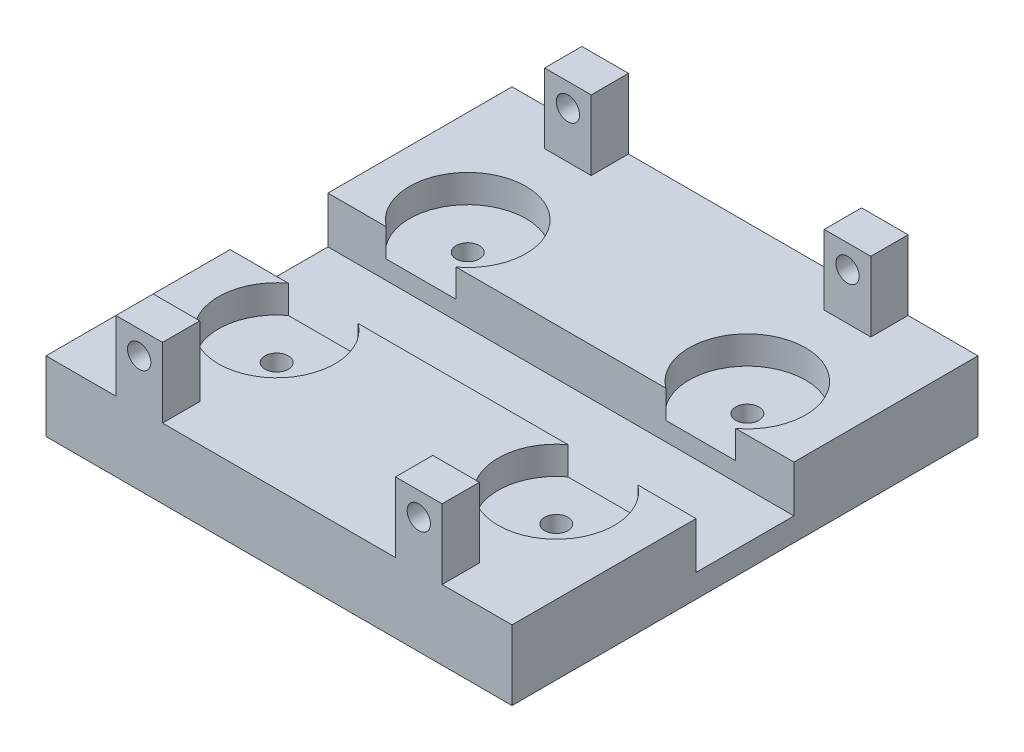
SolidWorks part; units mm, degrees
ref_plane "Front Plane" through (0, 0, 0) normal (0, 0, 1) x (1, 0, 0)
ref_plane "Top Plane" through (0, 0, 0) normal (0, 1, 0) x (1, 0, 0)
ref_plane "Right Plane" through (0, 0, 0) normal (1, 0, 0) x (0, 0, -1)
sketch "Sketch1" plane through (0, 0, 0) normal (0, 1, 0) x (1, 0, 0)
  line L1 (-907.2662, 39.6204) -> (92.7338, 39.6204)
  line L2 (-907.2662, 39.6204) -> (-907.2662, -960.3796)
  line L3 (-907.2662, -960.3796) -> (92.7338, -960.3796)
  line L4 (92.7338, 39.6204) -> (92.7338, -960.3796)
  dimension "D1" = 1000
  dimension "D2" = 1000
extrude "Boss-Extrude1" add sketch "Sketch1" along normal blind 300
sketch "Sketch2" plane through (0, 300, 0) normal (0, 1, 0) x (1, 0, 0)
  line L0 (-907.2662, 39.6204) -> (-907.2662, -960.3796) construction
  line L1 (-907.2662, -560.3796) -> (92.7338, -560.3796)
  line L2 (-907.2662, -560.3796) -> (-907.2662, -360.3796)
  line L3 (-907.2662, -360.3796) -> (92.7338, -360.3796)
  line L4 (92.7338, -560.3796) -> (92.7338, -360.3796)
  line L5 (92.7338, -960.3796) -> (92.7338, 39.6204) construction
  line L6 (92.7338, 39.6204) -> (-907.2662, 39.6204) construction
  line L7 (-907.2662, -960.3796) -> (92.7338, -960.3796) construction
  dimension "D1" = 400
  dimension "D2" = 400
extrude "Cut-Extrude1" cut sketch "Sketch2" against normal blind 100
other "Move Face1" face at (-407.2662, 0, 460.3796) parameters "D1"=150
scale "Scale1" bodies to scale 104 scale about centroid uniform scaling yes scale factor 0.1
sketch "Sketch5" plane through (0, 229.0385, 0) normal (0, 1, 0) x (1, 0, 0)
  line L0 (-457.2662, -410.3796) -> (-457.2662, -450.3796) construction
  line L1 (-357.2662, -410.3796) -> (-457.2662, -410.3796) construction
  circle A0 centre (-437.2662, -439.8796) radius 12.5
  dimension "D1" = 20
  dimension "D2" = 29.5
  dimension "D3" = 25
extrude "Cut-Extrude4" cut sketch "Sketch5" against normal blind 6 contours A0
sketch "Sketch11" plane through (0, 229.0385, 0) normal (0, 1, 0) x (1, 0, 0)
  line L0 (-357.2662, -450.3796) -> (-357.2662, -410.3796) construction
  line L1 (-357.2662, -410.3796) -> (-457.2662, -410.3796) construction
  circle A0 centre (-377.2662, -439.8796) radius 12.5
  dimension "D1" = 20
  dimension "D2" = 29.5
  dimension "D3" = 25
extrude "Cut-Extrude5" cut sketch "Sketch11" against normal blind 6 contours A0
sketch "Sketch12" plane through (0, 229.0385, 0) normal (0, 1, 0) x (1, 0, 0)
  line L0 (-357.2662, -510.3796) -> (-357.2662, -470.3796) construction
  line L1 (-457.2662, -510.3796) -> (-357.2662, -510.3796) construction
  circle A0 centre (-377.2662, -480.8796) radius 12.5
  dimension "D1" = 20
  dimension "D2" = 29.5
  dimension "D3" = 25
extrude "Cut-Extrude6" cut sketch "Sketch12" against normal blind 6 contours A0
sketch "Sketch13" plane through (0, 229.0385, 0) normal (0, 1, 0) x (1, 0, 0)
  line L0 (-457.2662, -470.3796) -> (-457.2662, -510.3796) construction
  line L1 (-457.2662, -510.3796) -> (-357.2662, -510.3796) construction
  circle A0 centre (-437.2662, -480.8796) radius 12.5
  dimension "D1" = 20
  dimension "D2" = 29.5
  dimension "D3" = 25
extrude "Cut-Extrude7" cut sketch "Sketch13" against normal blind 6 contours A0
sketch "Sketch14" plane through (0, 214.0385, 0) normal (0, -1, 0) x (-1, 0, 0)
  line L0 (357.2662, -510.3796) -> (357.2662, -410.3796) construction
  line L1 (377.2662, -444.5273) -> (381.2912, -442.2034)
  line L2 (381.2912, -442.2034) -> (381.2912, -437.5558)
  line L3 (381.2912, -437.5558) -> (377.2662, -435.2319)
  line L4 (377.2662, -435.2319) -> (373.2412, -437.5558)
  line L5 (373.2412, -437.5558) -> (373.2412, -442.2034)
  line L6 (373.2412, -442.2034) -> (377.2662, -444.5273)
  line L7 (357.2662, -410.3796) -> (457.2662, -410.3796) construction
  circle A0 centre (377.2662, -439.8796) radius 4.025 construction
  dimension "D3" = 8.05
  dimension "D1" = 20
  dimension "D2" = 29.5
extrude "Cut-Extrude8" cut sketch "Sketch14" against normal blind 3
sketch "Sketch15" plane through (0, 217.0385, 0) normal (0, -1, 0) x (-1, 0, 0)
  line L0 (357.2662, -510.3796) -> (357.2662, -410.3796) construction
  line L1 (357.2662, -410.3796) -> (457.2662, -410.3796) construction
  circle A0 centre (377.2662, -439.8796) radius 2.5
  dimension "D3" = 5
  dimension "D1" = 20
  dimension "D2" = 29.5
extrude "Cut-Extrude9" cut sketch "Sketch15" against normal blind 16
sketch "Sketch16" plane through (0, 214.0385, 0) normal (0, -1, 0) x (-1, 0, 0)
  line L0 (457.2662, -410.3796) -> (457.2662, -510.3796) construction
  line L1 (437.2662, -444.5273) -> (441.2912, -442.2034)
  line L2 (441.2912, -442.2034) -> (441.2912, -437.5558)
  line L3 (441.2912, -437.5558) -> (437.2662, -435.2319)
  line L4 (437.2662, -435.2319) -> (433.2412, -437.5558)
  line L5 (433.2412, -437.5558) -> (433.2412, -442.2034)
  line L6 (433.2412, -442.2034) -> (437.2662, -444.5273)
  line L7 (357.2662, -410.3796) -> (457.2662, -410.3796) construction
  circle A0 centre (437.2662, -439.8796) radius 4.025 construction
  dimension "D3" = 8.05
  dimension "D1" = 20
  dimension "D2" = 29.5
extrude "Cut-Extrude10" cut sketch "Sketch16" against normal blind 3
sketch "Sketch17" plane through (0, 217.0385, 0) normal (0, -1, 0) x (-1, 0, 0)
  line L0 (457.2662, -410.3796) -> (457.2662, -510.3796) construction
  line L1 (357.2662, -410.3796) -> (457.2662, -410.3796) construction
  circle A0 centre (437.2662, -439.8796) radius 2.5
  dimension "D1" = 20
  dimension "D3" = 5
  dimension "D2" = 29.5
extrude "Cut-Extrude11" cut sketch "Sketch17" against normal blind 10
sketch "Sketch18" plane through (0, 214.0385, 0) normal (0, -1, 0) x (-1, 0, 0)
  line L0 (357.2662, -510.3796) -> (357.2662, -410.3796) construction
  line L1 (377.2662, -485.5273) -> (381.2912, -483.2034)
  line L2 (381.2912, -483.2034) -> (381.2912, -478.5558)
  line L3 (381.2912, -478.5558) -> (377.2662, -476.2319)
  line L4 (377.2662, -476.2319) -> (373.2412, -478.5558)
  line L5 (373.2412, -478.5558) -> (373.2412, -483.2034)
  line L6 (373.2412, -483.2034) -> (377.2662, -485.5273)
  line L7 (457.2662, -510.3796) -> (357.2662, -510.3796) construction
  circle A0 centre (377.2662, -480.8796) radius 4.025 construction
  dimension "D3" = 8.05
  dimension "D1" = 20
  dimension "D2" = 29.5
extrude "Cut-Extrude12" cut sketch "Sketch18" against normal blind 3
sketch "Sketch19" plane through (0, 217.0385, 0) normal (0, -1, 0) x (-1, 0, 0)
  line L0 (357.2662, -510.3796) -> (357.2662, -410.3796) construction
  line L1 (457.2662, -510.3796) -> (357.2662, -510.3796) construction
  circle A0 centre (377.2662, -480.8796) radius 2.5
  dimension "D3" = 5
  dimension "D1" = 20
  dimension "D2" = 29.5
extrude "Cut-Extrude13" cut sketch "Sketch19" against normal blind 10
sketch "Sketch20" plane through (0, 214.0385, 0) normal (0, -1, 0) x (-1, 0, 0)
  line L0 (457.2662, -410.3796) -> (457.2662, -510.3796) construction
  line L1 (437.2662, -485.5273) -> (441.2912, -483.2034)
  line L2 (441.2912, -483.2034) -> (441.2912, -478.5558)
  line L3 (441.2912, -478.5558) -> (437.2662, -476.2319)
  line L4 (437.2662, -476.2319) -> (433.2412, -478.5558)
  line L5 (433.2412, -478.5558) -> (433.2412, -483.2034)
  line L6 (433.2412, -483.2034) -> (437.2662, -485.5273)
  line L7 (457.2662, -510.3796) -> (357.2662, -510.3796) construction
  circle A0 centre (437.2662, -480.8796) radius 4.025 construction
  dimension "D3" = 8.05
  dimension "D1" = 20
  dimension "D2" = 29.5
extrude "Cut-Extrude14" cut sketch "Sketch20" against normal blind 3
sketch "Sketch21" plane through (0, 217.0385, 0) normal (0, -1, 0) x (-1, 0, 0)
  line L0 (457.2662, -410.3796) -> (457.2662, -510.3796) construction
  line L1 (457.2662, -510.3796) -> (357.2662, -510.3796) construction
  circle A0 centre (437.2662, -480.8796) radius 2.5
  dimension "D3" = 5
  dimension "D1" = 20
  dimension "D2" = 29.5
extrude "Cut-Extrude15" cut sketch "Sketch21" against normal blind 10
sketch "Sketch27" plane through (0, 229.0385, 0) normal (0, 1, 0) x (1, 0, 0)
  line L0 (-457.2662, -510.3796) -> (-357.2662, -510.3796) construction
  line L1 (-432.2662, -502.3796) -> (-442.2662, -502.3796)
  line L2 (-432.2662, -502.3796) -> (-432.2662, -510.3796)
  line L3 (-432.2662, -510.3796) -> (-442.2662, -510.3796)
  line L4 (-442.2662, -502.3796) -> (-442.2662, -510.3796)
  line L5 (-432.2662, -502.3796) -> (-442.2662, -510.3796) construction
  line L6 (-432.2662, -510.3796) -> (-442.2662, -502.3796) construction
  line L7 (-457.2662, -470.3796) -> (-457.2662, -510.3796) construction
  point P0 (-437.2662, -506.3796)
  dimension "D1" = 0
  dimension "D2" = 15
  dimension "D3" = 25
  dimension "D4" = 8
extrude "Boss-Extrude3" add sketch "Sketch27" along normal blind 15
sketch "Sketch28" plane through (0, 0, 510.3796) normal (0, 0, 1) x (1, 0, 0)
  line L0 (-432.2662, 244.0385) -> (-432.2662, 229.0385) construction
  line L1 (-442.2662, 244.0385) -> (-432.2662, 244.0385) construction
  circle A0 centre (-437.2662, 239.0385) radius 2.5
  dimension "D1" = 5
  dimension "D2" = 5
  dimension "D3" = 5
extrude "Cut-Extrude21" cut sketch "Sketch28" against normal up to next
sketch "Sketch30" plane through (0, 229.0385, 0) normal (0, 1, 0) x (1, 0, 0)
  line L0 (-432.2662, -510.3796) -> (-357.2662, -510.3796) construction
  line L1 (-372.2662, -510.3796) -> (-382.2662, -510.3796)
  line L2 (-372.2662, -510.3796) -> (-372.2662, -502.3796)
  line L3 (-372.2662, -502.3796) -> (-382.2662, -502.3796)
  line L4 (-382.2662, -510.3796) -> (-382.2662, -502.3796)
  line L5 (-372.2662, -510.3796) -> (-382.2662, -502.3796) construction
  line L6 (-372.2662, -502.3796) -> (-382.2662, -510.3796) construction
  line L7 (-357.2662, -510.3796) -> (-357.2662, -470.3796) construction
  point P0 (-377.2662, -506.3796)
  dimension "D1" = 0
  dimension "D2" = 8
  dimension "D3" = 15
  dimension "D4" = 10
extrude "Boss-Extrude4" add sketch "Sketch30" along normal blind 15
sketch "Sketch31" plane through (0, 0, 510.3796) normal (0, 0, 1) x (1, 0, 0)
  line L0 (-372.2662, 244.0385) -> (-372.2662, 229.0385) construction
  line L1 (-382.2662, 244.0385) -> (-372.2662, 244.0385) construction
  circle A0 centre (-377.2662, 239.0385) radius 2.5
  dimension "D1" = 5
  dimension "D2" = 5
  dimension "D3" = 5
extrude "Cut-Extrude22" cut sketch "Sketch31" against normal blind 8
sketch "Sketch32" plane through (0, 229.0385, 0) normal (0, 1, 0) x (1, 0, 0)
  line L0 (-357.2662, -410.3796) -> (-457.2662, -410.3796) construction
  line L1 (-432.2662, -418.3796) -> (-442.2662, -418.3796)
  line L2 (-432.2662, -418.3796) -> (-432.2662, -410.3796)
  line L3 (-432.2662, -410.3796) -> (-442.2662, -410.3796)
  line L4 (-442.2662, -418.3796) -> (-442.2662, -410.3796)
  line L5 (-432.2662, -418.3796) -> (-442.2662, -410.3796) construction
  line L6 (-432.2662, -410.3796) -> (-442.2662, -418.3796) construction
  line L7 (-457.2662, -410.3796) -> (-457.2662, -450.3796) construction
  point P0 (-437.2662, -414.3796)
  point P9 (-442.2662, -414.3796)
  dimension "D1" = 0
  dimension "D2" = 15
  dimension "D3" = 10
  dimension "D4" = 8
extrude "Boss-Extrude5" add sketch "Sketch32" along normal blind 15
sketch "Sketch33" plane through (0, 0, 410.3796) normal (0, 0, -1) x (-1, 0, 0)
  line L0 (432.2662, 244.0385) -> (442.2662, 244.0385) construction
  line L1 (432.2662, 244.0385) -> (432.2662, 229.0385) construction
  circle A0 centre (437.2662, 239.0385) radius 2.5
  dimension "D1" = 5
  dimension "D2" = 5
  dimension "D3" = 5
extrude "Cut-Extrude23" cut sketch "Sketch33" against normal blind 8
sketch "Sketch34" plane through (0, 229.0385, 0) normal (0, 1, 0) x (1, 0, 0)
  line L0 (-357.2662, -410.3796) -> (-432.2662, -410.3796) construction
  line L1 (-372.2662, -418.3796) -> (-382.2662, -418.3796)
  line L2 (-372.2662, -418.3796) -> (-372.2662, -410.3796)
  line L3 (-372.2662, -410.3796) -> (-382.2662, -410.3796)
  line L4 (-382.2662, -418.3796) -> (-382.2662, -410.3796)
  line L5 (-372.2662, -418.3796) -> (-382.2662, -410.3796) construction
  line L6 (-372.2662, -410.3796) -> (-382.2662, -418.3796) construction
  line L7 (-357.2662, -450.3796) -> (-357.2662, -410.3796) construction
  point P0 (-377.2662, -414.3796)
  dimension "D1" = 0
  dimension "D2" = 10
  dimension "D3" = 15
  dimension "D4" = 8
extrude "Boss-Extrude6" add sketch "Sketch34" along normal blind 15
sketch "Sketch35" plane through (0, 0, 410.3796) normal (0, 0, -1) x (-1, 0, 0)
  line L0 (372.2662, 244.0385) -> (382.2662, 244.0385) construction
  line L1 (372.2662, 244.0385) -> (372.2662, 229.0385) construction
  circle A0 centre (377.2662, 239.0385) radius 2.5
  point P4 (377.2662, 244.0385)
  dimension "D1" = 5
  dimension "D2" = 5
  dimension "D3" = 5
extrude "Cut-Extrude24" cut sketch "Sketch35" against normal blind 8
sketch "Sketch40" plane through (0, 0, 470.3796) normal (0, 0, -1) x (-1, 0, 0)
  line L1 (357.2662, 219.0385) -> (457.2662, 219.0385)
  line L2 (357.2662, 219.0385) -> (357.2662, 229.0385)
  line L3 (357.2662, 229.0385) -> (457.2662, 229.0385)
  line L4 (457.2662, 219.0385) -> (457.2662, 229.0385)
extrude "Cut-Extrude25" cut sketch "Sketch40" against normal blind 0.5
sketch "Sketch41" plane through (0, 0, 450.3796) normal (0, 0, 1) x (1, 0, 0)
  line L1 (-457.2662, 219.0385) -> (-357.2662, 219.0385)
  line L2 (-457.2662, 219.0385) -> (-457.2662, 229.0385)
  line L3 (-457.2662, 229.0385) -> (-357.2662, 229.0385)
  line L4 (-357.2662, 219.0385) -> (-357.2662, 229.0385)
extrude "Cut-Extrude26" cut sketch "Sketch41" against normal blind 0.5
